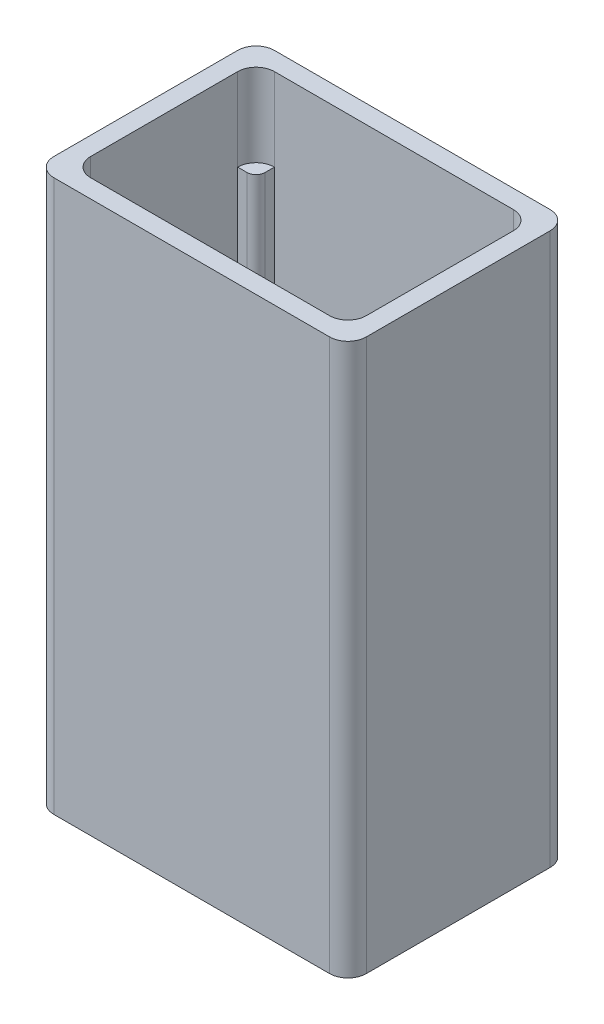
SolidWorks part; units mm, degrees
ref_plane "Front Plane" through (0, 0, 0) normal (0, 0, 1) x (1, 0, 0)
ref_plane "Top Plane" through (0, 0, 0) normal (0, 1, 0) x (1, 0, 0)
ref_plane "Right Plane" through (0, 0, 0) normal (1, 0, 0) x (0, 0, -1)
ref_plane "Plane1" through (0, 58, 0) normal (0, 1, 0) x (1, 0, 0)
sketch "Sketch8" plane through (0, 58, 0) normal (0, 1, 0) x (1, 0, 0)
  line L0 (-13, -10) -> (13, -10)
  line L1 (-15, -8) -> (-15, 8)
  line L2 (-13, 10) -> (13, 10)
  line L3 (15, -8) -> (15, 8)
  line L5 (-15, 10) -> (15, -10) construction
  line L6 (-15, -12) -> (15, -12)
  line L7 (-17, -10) -> (-17, 10)
  line L8 (-15, 12) -> (15, 12)
  line L9 (17, -10) -> (17, 10)
  line L11 (-17, 12) -> (17, -12) construction
  line L15 (0, 12) -> (0, -10) construction
  arc A0 (15, -8) -> (13, -10) centre (13, -8) cw
  arc A1 (-15, -8) -> (-13, -10) centre (-13, -8) ccw
  arc A4 (17, -10) -> (15, -12) centre (15, -10) cw
  arc A5 (-17, -10) -> (-15, -12) centre (-15, -10) ccw
  arc A6 (15, 12) -> (17, 10) centre (15, 10) cw
  arc A7 (-15, 12) -> (-17, 10) centre (-15, 10) ccw
  arc A8 (-13, 10) -> (-15, 8) centre (-13, 8) ccw
  arc A9 (13, 10) -> (15, 8) centre (13, 8) cw
  point P0 (0, 0)
  point P19 (-15, 10)
  point P26 (0, 0)
  point P27 (-12, 9.5)
  point P28 (15, 10)
  dimension "D3" = 2
  dimension "D6" = 2
  dimension "D2" = 34
  dimension "D7" = 2
  dimension "D1" = 30
  dimension "D4" = 24
  dimension "D5" = 20
sketch "Sketch11" plane through (0, 58, 0) normal (0, 1, 0) x (1, 0, 0)
  line L10 (-13, 10) -> (13, 10) construction
  line L11 (13, 10) -> (15, 10)
  line L14 (0, 12) -> (0, -10) construction
  line L15 (-13, 10) -> (-15, 10)
  line L16 (-13, 9) -> (-13, 10)
  line L17 (-15, 8) -> (-14, 8)
  line L18 (-15, 10) -> (-15, 8)
  line L19 (15, 10) -> (15, 6.9379)
  line L20 (15, 6.9379) -> (13.5, 6.9379)
  line L21 (13, 7.4379) -> (13, 10)
  arc A3 (-14, 8) -> (-13, 9) centre (-14, 9) ccw
  arc A4 (13.5, 6.9379) -> (13, 7.4379) centre (13.5, 7.4379) cw
  point P2 (12.6819, 10.154)
  point P7 (13, 9.9526)
  dimension "D1" = 0.5
extrude "Boss-Extrude4" add sketch "Sketch8" along normal blind 60
extrude "Boss-Extrude5" add sketch "Sketch11" along normal blind 51
